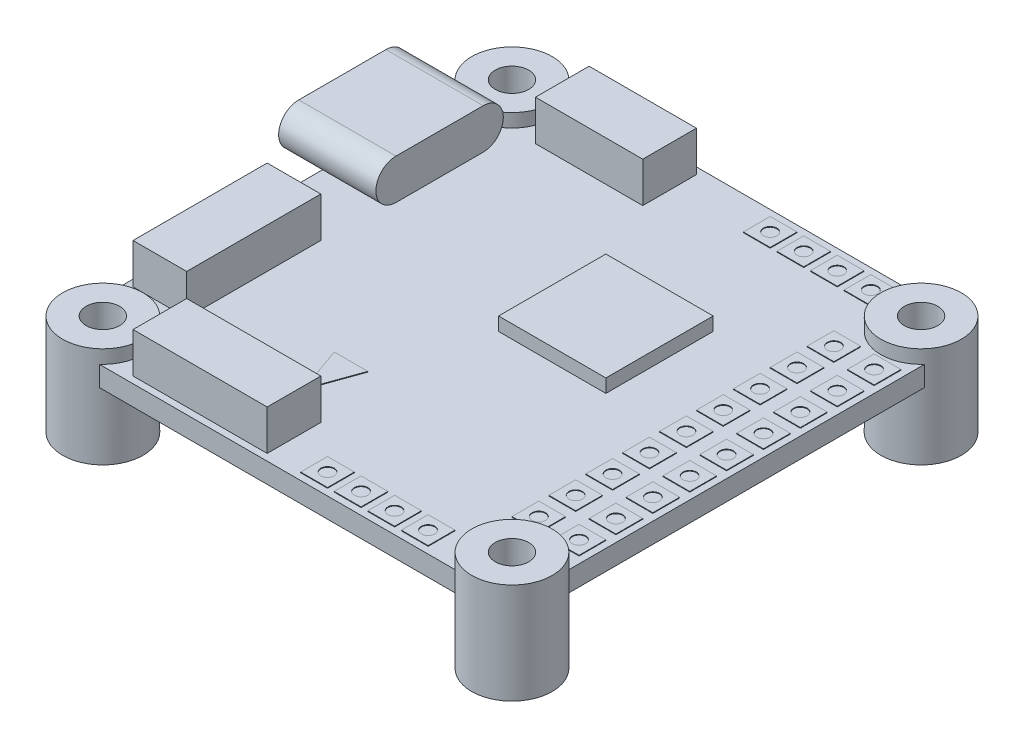
SolidWorks part; units mm, degrees
ref_plane "Front Plane" through (0, 0, 0) normal (0, 0, 1) x (1, 0, 0)
ref_plane "Top Plane" through (0, 0, 0) normal (0, 1, 0) x (1, 0, 0)
ref_plane "Right Plane" through (0, 0, 0) normal (1, 0, 0) x (0, 0, -1)
sketch "Sketch1" plane through (0, 0, 0) normal (0, 1, 0) x (1, 0, 0)
  line L0 (-13.2657, 17.5) -> (13.2657, 17.5)
  line L5 (-17.5, 13.2657) -> (-17.5, -13.2657)
  line L6 (17.5, 13.2657) -> (17.5, -13.2657)
  line L7 (-13.2657, -17.5) -> (13.2657, -17.5)
  arc A0 (-13.2657, 17.5) -> (-17.5, 13.2657) centre (-15.25, 15.25) ccw
  arc A1 (17.5, 13.2657) -> (13.2657, 17.5) centre (15.25, 15.25) ccw
  arc A2 (13.2657, -17.5) -> (17.5, -13.2657) centre (15.25, -15.25) ccw
  arc A3 (-17.5, -13.2657) -> (-13.2657, -17.5) centre (-15.25, -15.25) ccw
  dimension "D7" = 30.5
  dimension "D9" = 6
  dimension "D10" = 6
  dimension "D11" = 6
  dimension "D12" = 6
  dimension "D13" = 2.25
  dimension "D14" = 17.5
  dimension "D15" = 17.5
  dimension "D16" = 2.25
  dimension "D2" = 35
  dimension "D3" = 35
  dimension "D4" = 2.25
  dimension "D5" = 30.5
  dimension "D6" = 30.5
  dimension "D8" = 30.5
  dimension "D17" = 2.25
  dimension "D18" = 2.25
  dimension "D19" = 2.25
extrude "Boss-Extrude1" add sketch "Sketch1" along normal blind 1.5
sketch "Sketch2" plane through (0, 1.5, 0) normal (0, 1, 0) x (1, 0, 0)
  circle A0 centre (-15.25, 15.25) radius 3
  circle A1 centre (15.25, 15.25) radius 3
  circle A2 centre (15.25, -15.25) radius 3
  circle A3 centre (-15.25, -15.25) radius 3
extrude "Boss-Extrude2" add sketch "Sketch2" along normal blind 1 and the other way blind 6.5
sketch "Sketch3" plane through (0, 2.5, 0) normal (0, 1, 0) x (1, 0, 0)
  circle A0 centre (-15.25, -15.25) radius 1.25
  circle A1 centre (-15.25, 15.25) radius 1.25
  circle A2 centre (15.25, 15.25) radius 1.25
  circle A3 centre (15.25, -15.25) radius 1.25
  dimension "D1" = 2.5
  dimension "D2" = 2.5
  dimension "D3" = 2.5
  dimension "D4" = 2.5
extrude "Cut-Extrude1" cut sketch "Sketch3" against normal through all both and the other way through all
sketch "Sketch4" plane through (0, 1.5, 0) normal (0, 1, 0) x (1, 0, 0)
  line L1 (-11.25, 17) -> (-3.25, 17)
  line L2 (-11.25, 17) -> (-11.25, 13)
  line L3 (-11.25, 13) -> (-3.25, 13)
  line L4 (-3.25, 17) -> (-3.25, 13)
  line L5 (-17.5, 13.2657) -> (-17.5, -13.2657) construction
  line L6 (-17, -1.25) -> (-13, -1.25)
  line L7 (-17, -1.25) -> (-17, -11.25)
  line L8 (-17, -11.25) -> (-13, -11.25)
  line L9 (-13, -1.25) -> (-13, -11.25)
  line L10 (-11.25, -13) -> (-1.25, -13)
  line L11 (-11.25, -13) -> (-11.25, -17)
  line L12 (-11.25, -17) -> (-1.25, -17)
  line L13 (-1.25, -13) -> (-1.25, -17)
  line L14 (-13.2657, -17.5) -> (13.2657, -17.5) construction
  line L15 (13.2657, 17.5) -> (-13.2657, 17.5) construction
  circle A0 centre (-15.25, 15.25) radius 3 construction
  arc A1 (-13.2657, -17.5) -> (-17.5, -13.2657) centre (-15.25, -15.25) ccw construction
  dimension "D3" = 4
  dimension "D10" = 4
  dimension "D1" = 8
  dimension "D2" = 4
  dimension "D4" = 0.5
  dimension "D5" = 0.5
  dimension "D6" = 10
  dimension "D7" = 4
  dimension "D8" = 10
  dimension "D9" = 4
  dimension "D11" = 4
  dimension "D12" = 0.5
extrude "Boss-Extrude3" add sketch "Sketch4" along normal blind 3
sketch "Sketch5" plane through (0, 1.5, 0) normal (0, 1, 0) x (1, 0, 0)
  line L0 (13.2657, 17.5) -> (-13.2657, 17.5) construction
  line L1 (-0.5, 7.5) -> (7.5, 7.5)
  line L2 (-0.5, 7.5) -> (-0.5, -0.5)
  line L3 (-0.5, -0.5) -> (7.5, -0.5)
  line L4 (7.5, 7.5) -> (7.5, -0.5)
  line L5 (17.5, -13.2657) -> (17.5, 13.2657) construction
  dimension "D1" = 10
  dimension "D2" = 10
  dimension "D3" = 8
  dimension "D4" = 8
extrude "Boss-Extrude4" add sketch "Sketch5" along normal blind 1
sketch "Sketch6" plane through (-17.5, 0, 0) normal (-1, 0, 0) x (0, 0, 1)
  line L1 (-10.1046, 4.897) -> (-3.6046, 4.897)
  line L3 (-10.1046, 1.897) -> (-3.6046, 1.897)
  line L5 (-10.1046, 4.647) -> (-3.6046, 4.647)
  line L7 (-10.1046, 2.147) -> (-3.6046, 2.147)
  line L8 (-9.7546, 3.522) -> (-3.9546, 3.522)
  line L9 (-9.8546, 3.422) -> (-9.8546, 3.372)
  line L10 (-9.7546, 3.272) -> (-3.9546, 3.272)
  line L11 (-3.8546, 3.422) -> (-3.8546, 3.372)
  arc A0 (-10.1046, 4.897) -> (-10.1046, 1.897) centre (-10.1046, 3.397) ccw
  arc A1 (-3.6046, 1.897) -> (-3.6046, 4.897) centre (-3.6046, 3.397) ccw
  arc A2 (-10.1046, 4.647) -> (-10.1046, 2.147) centre (-10.1046, 3.397) ccw
  arc A3 (-3.6046, 2.147) -> (-3.6046, 4.647) centre (-3.6046, 3.397) ccw
  arc A4 (-9.8546, 3.372) -> (-9.7546, 3.272) centre (-9.7546, 3.372) ccw
  arc A5 (-9.7546, 3.522) -> (-9.8546, 3.422) centre (-9.7546, 3.422) ccw
  arc A6 (-3.9546, 3.272) -> (-3.8546, 3.372) centre (-3.9546, 3.372) ccw
  arc A7 (-3.9546, 3.522) -> (-3.8546, 3.422) centre (-3.9546, 3.422) cw
  point P16 (-9.8546, 3.272)
  point P21 (-3.8546, 3.272)
  dimension "D9" = 0.1
  dimension "D1" = 0.25
  dimension "D2" = 3
  dimension "D3" = 0.25
  dimension "D4" = 6.5
  dimension "D5" = 0.25
  dimension "D6" = 6
  dimension "D7" = 0.25
  dimension "D8" = 0.125
extrude "Boss-Extrude5" add sketch "Sketch6" along normal blind 2 and the other way blind 5 separate body contours L3 A1 L1 A0 A3 L7 A2 L5 | A7 L8 A5 L9 A4 L10 A6 L11
sketch "Sketch7" plane through (-12.5, 0, 0) normal (1, 0, 0) x (0, 0, -1)
  line L0 (3.6046, 4.897) -> (10.1046, 4.897)
  line L1 (3.6046, 1.897) -> (10.1046, 1.897)
  arc A2 (10.1046, 1.897) -> (10.1046, 4.897) centre (10.1046, 3.397) ccw
  arc A3 (3.6046, 4.897) -> (3.6046, 1.897) centre (3.6046, 3.397) ccw
extrude "Boss-Extrude6" add sketch "Sketch7" along normal blind 0.25
sketch "Sketch8" plane through (0, 1.5, 0) normal (0, 1, 0) x (1, 0, 0)
  line L0 (-5.25, -8) -> (-4, -11.5)
  line L1 (-4, -11.5) -> (-2.75, -8)
  line L2 (-2.75, -8) -> (-5.25, -8)
  line L3 (-1.25, -13) -> (-11.25, -13) construction
  line L4 (-13, -11.25) -> (-13, -1.25) construction
  point P3 (-5.3736, -6.4594)
  dimension "D1" = 3.5
  dimension "D2" = 2.5
  dimension "D3" = 1.25
  dimension "D4" = 1.5
  dimension "D5" = 9
extrude "Boss-Extrude7" add sketch "Sketch8" along normal blind 0.05
sketch "Sketch9" plane through (0, 1.5, 0) normal (0, 1, 0) x (1, 0, 0)
  line L0 (-13.2657, -17.5) -> (13.2657, -17.5) construction
  line L1 (1.25, -15) -> (3.25, -15)
  line L2 (1.25, -15) -> (1.25, -17)
  line L3 (1.25, -17) -> (3.25, -17)
  line L4 (3.25, -15) -> (3.25, -17)
  line L5 (3.75, -15) -> (5.75, -15)
  line L6 (3.75, -15) -> (3.75, -17)
  line L7 (3.75, -17) -> (5.75, -17)
  line L8 (5.75, -15) -> (5.75, -17)
  line L9 (6.25, -15) -> (8.25, -15)
  line L10 (6.25, -15) -> (6.25, -17)
  line L11 (6.25, -17) -> (8.25, -17)
  line L12 (8.25, -15) -> (8.25, -17)
  line L13 (8.75, -15) -> (10.75, -15)
  line L14 (8.75, -15) -> (8.75, -17)
  line L15 (8.75, -17) -> (10.75, -17)
  line L16 (10.75, -15) -> (10.75, -17)
  line L17 (17.5, -13.2657) -> (17.5, 13.2657) construction
  line L18 (17, 12) -> (15, 12)
  line L19 (17, 12) -> (17, 10)
  line L20 (17, 10) -> (15, 10)
  line L21 (15, 12) -> (15, 10)
  line L22 (14, 12) -> (12, 12)
  line L23 (14, 12) -> (14, 10)
  line L24 (14, 10) -> (12, 10)
  line L25 (12, 12) -> (12, 10)
  line L26 (17, 6.5) -> (15, 6.5)
  line L27 (17, 6.5) -> (17, 4.5)
  line L28 (17, 4.5) -> (15, 4.5)
  line L29 (15, 6.5) -> (15, 4.5)
  line L30 (14, 6.5) -> (12, 6.5)
  line L31 (14, 6.5) -> (14, 4.5)
  line L32 (14, 4.5) -> (12, 4.5)
  line L33 (12, 6.5) -> (12, 4.5)
  line L34 (17, 3.75) -> (15, 3.75)
  line L35 (17, 3.75) -> (17, 1.75)
  line L36 (17, 1.75) -> (15, 1.75)
  line L37 (15, 3.75) -> (15, 1.75)
  line L38 (14, 3.75) -> (12, 3.75)
  line L39 (14, 3.75) -> (14, 1.75)
  line L40 (14, 1.75) -> (12, 1.75)
  line L41 (12, 3.75) -> (12, 1.75)
  line L42 (17, 9.25) -> (15, 9.25)
  line L43 (17, 9.25) -> (17, 7.25)
  line L44 (17, 7.25) -> (15, 7.25)
  line L45 (15, 9.25) -> (15, 7.25)
  line L46 (14, 9.25) -> (12, 9.25)
  line L47 (14, 9.25) -> (14, 7.25)
  line L48 (14, 7.25) -> (12, 7.25)
  line L49 (12, 9.25) -> (12, 7.25)
  line L50 (17, 1) -> (15, 1)
  line L51 (17, 1) -> (17, -1)
  line L52 (17, -1) -> (15, -1)
  line L53 (15, 1) -> (15, -1)
  line L54 (14, 1) -> (12, 1)
  line L55 (14, 1) -> (14, -1)
  line L56 (14, -1) -> (12, -1)
  line L57 (12, 1) -> (12, -1)
  line L66 (17, -1.75) -> (15, -1.75)
  line L67 (17, -1.75) -> (17, -3.75)
  line L68 (17, -3.75) -> (15, -3.75)
  line L69 (15, -1.75) -> (15, -3.75)
  line L70 (14, -1.75) -> (12, -1.75)
  line L71 (14, -1.75) -> (14, -3.75)
  line L72 (14, -3.75) -> (12, -3.75)
  line L73 (12, -1.75) -> (12, -3.75)
  line L74 (17, -4.5) -> (15, -4.5)
  line L75 (17, -4.5) -> (17, -6.5)
  line L76 (17, -6.5) -> (15, -6.5)
  line L77 (15, -4.5) -> (15, -6.5)
  line L78 (14, -4.5) -> (12, -4.5)
  line L79 (14, -4.5) -> (14, -6.5)
  line L80 (14, -6.5) -> (12, -6.5)
  line L81 (12, -4.5) -> (12, -6.5)
  line L82 (17, -7.25) -> (15, -7.25)
  line L83 (17, -7.25) -> (17, -9.25)
  line L84 (17, -9.25) -> (15, -9.25)
  line L85 (15, -7.25) -> (15, -9.25)
  line L86 (14, -7.25) -> (12, -7.25)
  line L87 (14, -7.25) -> (14, -9.25)
  line L88 (14, -9.25) -> (12, -9.25)
  line L89 (12, -7.25) -> (12, -9.25)
  line L90 (17, -10) -> (15, -10)
  line L91 (17, -10) -> (17, -12)
  line L92 (17, -12) -> (15, -12)
  line L93 (15, -10) -> (15, -12)
  line L94 (14, -10) -> (12, -10)
  line L95 (14, -10) -> (14, -12)
  line L96 (14, -12) -> (12, -12)
  line L97 (12, -10) -> (12, -12)
  line L98 (2.25, 17) -> (4.25, 17)
  line L99 (2.25, 17) -> (2.25, 15)
  line L100 (2.25, 15) -> (4.25, 15)
  line L101 (4.25, 17) -> (4.25, 15)
  line L102 (4.75, 17) -> (6.75, 17)
  line L103 (4.75, 17) -> (4.75, 15)
  line L104 (4.75, 15) -> (6.75, 15)
  line L105 (6.75, 17) -> (6.75, 15)
  line L106 (7.25, 17) -> (9.25, 17)
  line L107 (7.25, 17) -> (7.25, 15)
  line L108 (7.25, 15) -> (9.25, 15)
  line L109 (9.25, 17) -> (9.25, 15)
  line L110 (9.75, 17) -> (11.75, 17)
  line L111 (9.75, 17) -> (9.75, 15)
  line L112 (9.75, 15) -> (11.75, 15)
  line L113 (11.75, 17) -> (11.75, 15)
  line L114 (13.2657, 17.5) -> (-13.2657, 17.5) construction
  circle A0 centre (16, 2.75) radius 0.5
  circle A1 centre (15.25, -15.25) radius 1.25 construction
  circle A2 centre (2.25, -16) radius 0.5
  circle A3 centre (4.75, -16) radius 0.5
  circle A4 centre (7.25, -16) radius 0.5
  circle A5 centre (9.75, -16) radius 0.5
  circle A6 centre (16, 11) radius 0.5
  circle A7 centre (13, 11) radius 0.5
  circle A8 centre (16, 5.5) radius 0.5
  circle A9 centre (13, 5.5) radius 0.5
  circle A10 centre (13, 2.75) radius 0.5
  circle A11 centre (16, 8.25) radius 0.5
  circle A12 centre (13, 8.25) radius 0.5
  circle A13 centre (16, 0) radius 0.5
  circle A14 centre (13, 0) radius 0.5
  circle A17 centre (15.25, 15.25) radius 1.25 construction
  circle A18 centre (15.25, 15.25) radius 3 construction
  circle A19 centre (16, -5.5) radius 0.5
  circle A20 centre (16, -2.75) radius 0.5
  circle A21 centre (13, -2.75) radius 0.5
  circle A22 centre (13, -5.5) radius 0.5
  circle A23 centre (16, -8.25) radius 0.5
  circle A24 centre (13, -8.25) radius 0.5
  circle A25 centre (16, -11) radius 0.5
  circle A26 centre (13, -11) radius 0.5
  circle A27 centre (3.25, 16) radius 0.5
  circle A28 centre (5.75, 16) radius 0.5
  circle A29 centre (8.25, 16) radius 0.5
  circle A30 centre (10.75, 16) radius 0.5
  dimension "D17" = 1
  dimension "D18" = 1
  dimension "D19" = 1
  dimension "D20" = 1
  dimension "D22" = 1
  dimension "D23" = 1
  dimension "D24" = 1
  dimension "D25" = 1
  dimension "D26" = 1
  dimension "D27" = 1
  dimension "D28" = 1
  dimension "D35" = 1
  dimension "D36" = 1
  dimension "D38" = 1
  dimension "D39" = 1
  dimension "D40" = 1
  dimension "D46" = 1
  dimension "D47" = 1
  dimension "D57" = 1
  dimension "D58" = 1
  dimension "D68" = 1
  dimension "D69" = 1
  dimension "D79" = 1
  dimension "D80" = 1
  dimension "D90" = 0.5
  dimension "D91" = 0.5
  dimension "D96" = 3.25
  dimension "D112" = 1
  dimension "D113" = 1
  dimension "D123" = 1
  dimension "D124" = 1
  dimension "D134" = 1
  dimension "D135" = 1
  dimension "D151" = 1
  dimension "D152" = 1
  dimension "D161" = 1
  dimension "D162" = 1
  dimension "D163" = 1
  dimension "D164" = 1
  dimension "D1" = 2
  dimension "D2" = 2
  dimension "D3" = 2
  dimension "D4" = 2
  dimension "D5" = 0.5
  dimension "D6" = 0.5
  dimension "D7" = 0.5
  dimension "D8" = 2
  dimension "D9" = 2
  dimension "D10" = 2
  dimension "D11" = 2
  dimension "D12" = 4.5
  dimension "D13" = 0.5
  dimension "D14" = 0.5
  dimension "D15" = 0.5
  dimension "D16" = 0.5
  dimension "D21" = 1
  dimension "D29" = 2
  dimension "D30" = 2
  dimension "D31" = 2
  dimension "D32" = 2
  dimension "D33" = 0.5
  dimension "D34" = 1
  dimension "D37" = 1
  dimension "D41" = 2
  dimension "D42" = 2
  dimension "D43" = 2
  dimension "D44" = 2
  dimension "D45" = 1
  dimension "D48" = 1
  dimension "D49" = 1
  dimension "D50" = 1
  dimension "D51" = 1
  dimension "D52" = 2
  dimension "D53" = 2
  dimension "D54" = 2
  dimension "D55" = 2
  dimension "D56" = 1
  dimension "D59" = 1
  dimension "D60" = 1
  dimension "D61" = 1
  dimension "D62" = 1
  dimension "D63" = 2
  dimension "D64" = 2
  dimension "D65" = 2
  dimension "D66" = 2
  dimension "D67" = 1
  dimension "D70" = 1
  dimension "D71" = 1
  dimension "D72" = 1
  dimension "D73" = 1
  dimension "D74" = 2
  dimension "D75" = 2
  dimension "D76" = 2
  dimension "D77" = 2
  dimension "D78" = 1
  dimension "D81" = 1
  dimension "D82" = 1
  dimension "D83" = 1
  dimension "D84" = 1
  dimension "D85" = 2
  dimension "D86" = 2
  dimension "D87" = 2
  dimension "D88" = 2
  dimension "D89" = 0.5
  dimension "D92" = 2
  dimension "D93" = 2
  dimension "D94" = 2
  dimension "D95" = 2
  dimension "D97" = 0.75
  dimension "D98" = 0.75
  dimension "D99" = 3.25
  dimension "D100" = 0.5
  dimension "D101" = 0.75
  dimension "D102" = 0.5
  dimension "D103" = 0.75
  dimension "D104" = 0.5
  dimension "D105" = 0.75
  dimension "D106" = 0.5
  dimension "D107" = 2
  dimension "D108" = 2
  dimension "D109" = 2
  dimension "D110" = 2
  dimension "D111" = 1
  dimension "D114" = 1
  dimension "D115" = 1
  dimension "D116" = 1
  dimension "D117" = 1
  dimension "D118" = 2
  dimension "D119" = 2
  dimension "D120" = 2
  dimension "D121" = 2
  dimension "D122" = 1
  dimension "D125" = 1
  dimension "D126" = 1
  dimension "D127" = 1
  dimension "D128" = 1
  dimension "D129" = 2
  dimension "D130" = 2
  dimension "D131" = 2
  dimension "D132" = 2
  dimension "D133" = 1
  dimension "D136" = 1
  dimension "D137" = 1
  dimension "D138" = 1
  dimension "D139" = 1
  dimension "D140" = 0.75
  dimension "D141" = 0.75
  dimension "D142" = 0.75
  dimension "D143" = 0.75
  dimension "D144" = 0.75
  dimension "D145" = 0.75
  dimension "D146" = 2
  dimension "D147" = 2
  dimension "D148" = 2
  dimension "D149" = 2
  dimension "D150" = 1
  dimension "D153" = 1
  dimension "D154" = 1
  dimension "D155" = 1
  dimension "D156" = 1
  dimension "D157" = 0.75
  dimension "D158" = 0.5
  dimension "D159" = 0.5
  dimension "D160" = 0.75
  dimension "D165" = 1
  dimension "D166" = 1
  dimension "D167" = 1
  dimension "D168" = 1
  dimension "D169" = 1
  dimension "D170" = 1
  dimension "D171" = 1
  dimension "D172" = 1
  dimension "D173" = 3.5
  dimension "D174" = 0.5
  dimension "D175" = 0.5
  dimension "D176" = 0.5
  dimension "D177" = 0.5
  dimension "D178" = 0.75
extrude "Boss-Extrude8" add sketch "Sketch9" along normal blind 0.05
